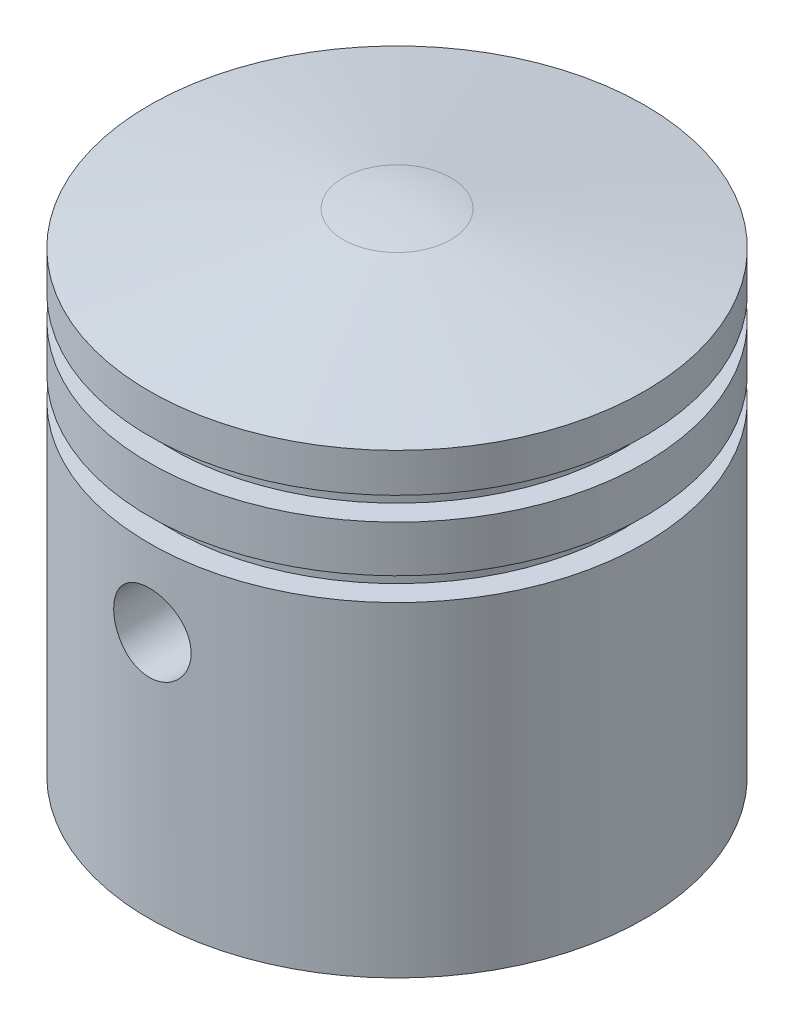
SolidWorks part; units mm, degrees
ref_plane "Front Plane" through (0, 0, 0) normal (0, 0, 1) x (1, 0, 0)
ref_plane "Top Plane" through (0, 0, 0) normal (0, 1, 0) x (1, 0, 0)
ref_plane "Right Plane" through (0, 0, 0) normal (1, 0, 0) x (0, 0, -1)
sketch "Sketch1" plane through (0, 0, 0) normal (0, 0, 1) x (1, 0, 0)
  line L0 (0, 0) -> (0, 10222.4892) construction
  line L1 (-1032, 0) -> (-16, 0) construction
  line L2 (13, 0) -> (13, 10)
  line L3 (13, 10) -> (10, 10)
  line L4 (10, 10) -> (10, 24)
  line L5 (10, 24) -> (0, 24)
  line L6 (0, 24) -> (0, 32)
  line L7 (3.473, 31.7233) -> (16, 29.5144)
  line L8 (16, 29.5144) -> (16, 27)
  line L9 (16, 27) -> (14.5, 27)
  line L10 (14.5, 27) -> (14.5, 25.5)
  line L11 (14.5, 25.5) -> (16, 25.5)
  line L12 (16, 25.5) -> (16, 22.5)
  line L13 (16, 22.5) -> (14.5, 22.5)
  line L14 (14.5, 22.5) -> (14.5, 21)
  line L15 (14.5, 21) -> (16, 21)
  line L16 (16, 21) -> (16, 0)
  line L17 (13, 0) -> (16, 0)
  line L32 (-13, 0) -> (10222.4892, 0) construction
  line L33 (0, 32) -> (0, 32.0271)
  arc A0 (3.473, 31.7233) -> (0, 32.0271) centre (0, 12.0271) ccw
  point P23 (0, 0)
  dimension "D14" = 20
  dimension "D15" = 12.7203
  dimension "D1" = 13
  dimension "D2" = 10
  dimension "16" = 16
  dimension "D3" = 21
  dimension "D4" = 32
  dimension "D5" = 1.5
  dimension "D6" = 1.5
  dimension "D7" = 3
  dimension "D8" = 0
  dimension "D9" = 10
  dimension "D10" = 10
  dimension "D11" = 24
  dimension "D12" = 16
  dimension "D13" = 14.5
revolve "Revolve2" add sketch "Sketch1" angle 360 about L0
sketch "Sketch2" plane through (0, 0, 0) normal (0, 0, 1) x (1, 0, 0)
  circle A0 centre (0, 16) radius 2.5
  point P2 (0, 0)
  dimension "D1" = 5
  dimension "D2" = 16
extrude "Cut-Extrude1" cut sketch "Sketch2" against normal blind 50 and the other way blind 39
